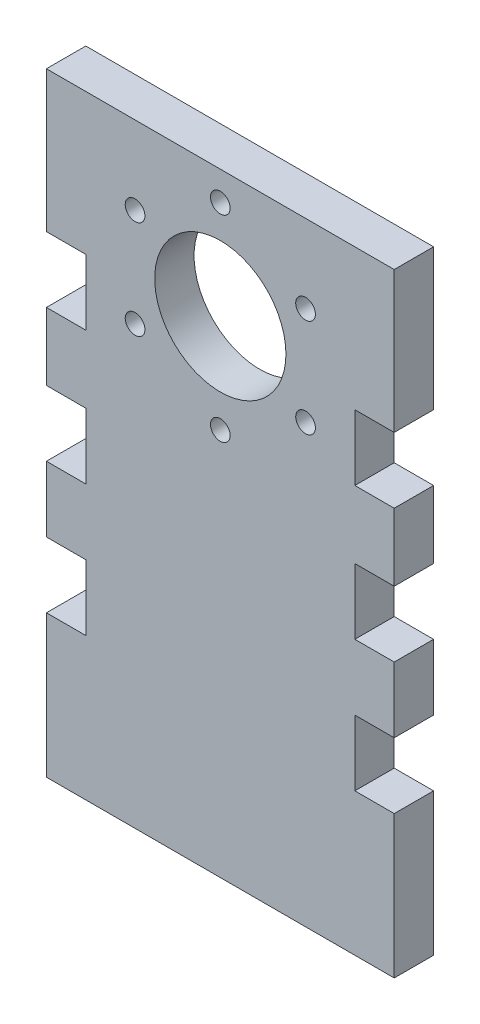
SolidWorks part; units mm, degrees
ref_plane "Alzado" through (0, 0, 0) normal (0, 0, 1) x (1, 0, 0)
ref_plane "Planta" through (0, 0, 0) normal (0, 1, 0) x (1, 0, 0)
ref_plane "Vista lateral" through (0, 0, 0) normal (1, 0, 0) x (0, 0, -1)
sketch "Sketch1" plane through (0, 0, 0) normal (0, 0, 1) x (1, 0, 0)
  line L0 (-13.25, 15.5) -> (-10.25, 15.5)
  line L1 (-13.25, 20.5) -> (13.25, 20.5) construction
  line L2 (-13.25, 20.5) -> (-13.25, 15.5)
  line L3 (-13.25, -20.5) -> (13.25, -20.5)
  line L4 (13.25, 20.5) -> (13.25, 15.5)
  line L5 (-13.25, 20.5) -> (13.25, -20.5) construction
  line L6 (-13.25, -20.5) -> (13.25, 20.5) construction
  line L7 (-10.25, 15.5) -> (-10.25, 10.5)
  line L8 (-10.25, 10.5) -> (-13.25, 10.5)
  line L9 (-13.25, 5.35) -> (-10.25, 5.35)
  line L10 (-10.25, 5.35) -> (-10.25, 0.35)
  line L11 (-10.25, 0.35) -> (-13.25, 0.35)
  line L12 (-13.25, -4.65) -> (-10.25, -4.65)
  line L13 (-10.25, -4.65) -> (-10.25, -9.65)
  line L14 (-10.25, -9.65) -> (-13.25, -9.65)
  line L15 (0, 20.5) -> (0, -20.5) construction
  line L16 (10.25, -9.65) -> (13.25, -9.65)
  line L17 (10.25, -4.65) -> (10.25, -9.65)
  line L18 (13.25, -4.65) -> (10.25, -4.65)
  line L19 (10.25, 0.35) -> (13.25, 0.35)
  line L20 (10.25, 5.35) -> (10.25, 0.35)
  line L21 (13.25, 5.35) -> (10.25, 5.35)
  line L22 (10.25, 10.5) -> (13.25, 10.5)
  line L23 (10.25, 15.5) -> (10.25, 10.5)
  line L24 (13.25, 15.5) -> (10.25, 15.5)
  line L25 (-13.25, 10.5) -> (-13.25, 5.35)
  line L26 (-13.25, 0.35) -> (-13.25, -4.65)
  line L27 (-13.25, -9.65) -> (-13.25, -20.5)
  line L28 (13.25, -9.65) -> (13.25, -20.5)
  line L29 (13.25, 0.35) -> (13.25, -4.65)
  line L30 (13.25, 10.5) -> (13.25, 5.35)
  line L31 (-6.4952, 20.29) -> (6.4952, 12.79) construction
  line L32 (6.4953, 20.2898) -> (-6.4953, 12.7902) construction
  line L33 (-13.25, 20.5) -> (-13.25, 26.25)
  line L34 (-13.25, 26.25) -> (13.25, 26.25)
  line L35 (13.25, 26.25) -> (13.25, 20.5)
  circle A0 centre (0, 16.54) radius 5
  circle A1 centre (0, 16.54) radius 7.5 construction
  circle A2 centre (0, 24.04) radius 0.75
  circle A3 centre (6.4953, 20.2898) radius 0.75
  circle A4 centre (6.4952, 12.79) radius 0.75
  circle A5 centre (0, 9.04) radius 0.75
  circle A6 centre (-6.4953, 12.7902) radius 0.75
  circle A7 centre (-6.4952, 20.29) radius 0.75
  point P0 (0, 0)
  point P49 (0, 16.54)
  point P50 (0, 16.54)
  dimension "D8" = 10
  dimension "D10" = 15
  dimension "D11" = 1.5
  dimension "D1" = 26.5
  dimension "D2" = 41
  dimension "D3" = 3
  dimension "D4" = 5
  dimension "D5" = 5
  dimension "D6" = 5.15
  dimension "D7" = 5
  dimension "D9" = 37.04
  dimension "D12" = 60
  dimension "D13" = 59.998
  dimension "D14" = 5.75
extrude "Boss-Extrude1" add sketch "Sketch1" along normal blind 3
